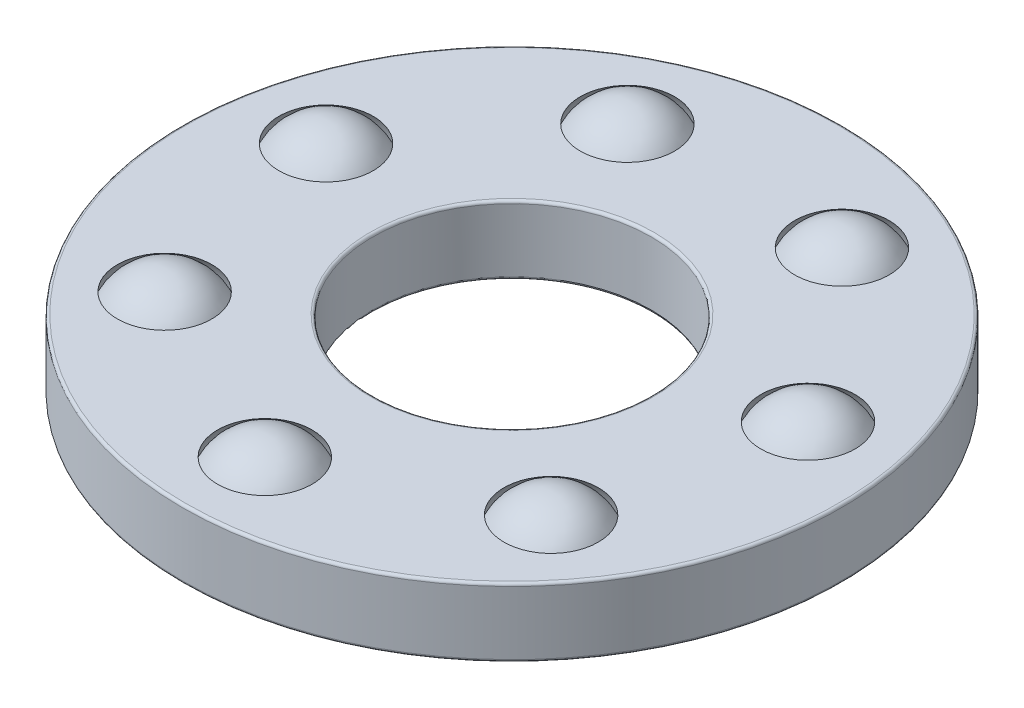
SolidWorks part; units mm, degrees
ref_plane "Front Plane" through (0, 0, 0) normal (0, 0, 1) x (1, 0, 0)
ref_plane "Top Plane" through (0, 0, 0) normal (0, 1, 0) x (1, 0, 0)
ref_plane "Right Plane" through (0, 0, 0) normal (1, 0, 0) x (0, 0, -1)
sketch "Sketch1" plane through (0, 0, 0) normal (1, 0, 0) x (0, 0, -1)
  line L0 (-6, 0) -> (6, 0) construction
  line L1 (0, -2.46) -> (0, 2.46) construction
  line L2 (-6, 0.625) -> (-2.538, 0.625)
  line L3 (-6, 0.625) -> (-6, -0.625)
  line L4 (-6, -0.625) -> (-2.538, -0.625)
  line L5 (-2.538, 0.625) -> (-2.538, -0.625)
  line L6 (-4.5, 1) -> (-4.5, -1) construction
  circle A0 centre (-4.5, 0) radius 1 construction
  dimension "D2" = 1.25
revolve "Revolve1" add sketch "Sketch1" angle 360 about L1
sketch "Sketch3" plane through (0, 0, 0) normal (1, 0, 0) x (0, 0, -1)
  line L0 (-4.5, 1.0625) -> (-4.5, -1.0625)
  line L1 (-4.5, 1) -> (-4.5, -1) construction
  line L2 (-4.4375, 1.0607) -> (-4.4375, -1.0607) construction
  arc A0 (-4.5, 1) -> (-4.5, -1) centre (-4.5, 0) ccw construction
  circle A1 centre (-4.5, 0) radius 1 construction
  arc A2 (-4.5, 1.0625) -> (-4.5, -1.0625) centre (-4.5, 0) ccw
  arc A3 (-4.4375, 1.0607) -> (-4.4375, -1.0607) centre (-4.5, 0) ccw construction
  dimension "D1" = 0.0625
revolve "Cut-Revolve1" cut sketch "Sketch3" angle 360 about L0
sketch "Sketch2" plane through (0, 0, 0) normal (1, 0, 0) x (0, 0, -1)
  line L0 (-4.5, 1) -> (-4.5, -1)
  arc A0 (-4.5, 1) -> (-4.5, -1) centre (-4.5, 0) ccw
  circle A2 centre (-4.5, 0) radius 1 construction
revolve "Revolve2" add sketch "Sketch2" angle 360 about L0
ref_axis "Axis1" through (0, 2.46, 0) along (0, -1, 0)
pattern_circular "CirPattern1" count 7 every 51.429 about axis through (0, 2.46, 0) along (0, -1, 0) of bodies 187
pattern_circular "CirPattern2" count 7 every 51.429 about axis through (0, 0, 0) along (0, 1, 0) of "Cut-Revolve1"
sketch "Sketch4" plane through (0, 0, 0) normal (1, 0, 0) x (0, 0, -1)
  line L0 (-6, 0.625) -> (-6, -0.625) construction
  line L1 (-6, 1) -> (-2.538, 1)
  line L2 (-6, 1) -> (-6, 2.46)
  line L3 (-6, 2.46) -> (-2.538, 2.46)
  line L4 (-2.538, 1) -> (-2.538, 2.46)
  line L5 (-6, -2.46) -> (-2.538, -2.46)
  line L6 (-6, -2.46) -> (-6, -1)
  line L7 (-6, -1) -> (-2.538, -1)
  line L8 (-2.538, -2.46) -> (-2.538, -1)
  line L10 (-2.538, 0.625) -> (-2.538, -0.625) construction
  line L11 (0, 0) -> (-6, 0) construction
  line L12 (-6, 0) -> (6, 0) construction
  dimension "Ht" = 4.92
  dimension "Washer Thickness" = 1.46
revolve "Revolve3" add sketch "Sketch4" angle 360 about L1
fillet "Fillet1" radius 0.0492 4 edges at (0, 1, -2.538) (0, 2.46, -2.538) (0, 1, -6) (0, 2.46, -6)
fillet "Fillet2" radius 0.0492 4 edges at (0, -0.625, -2.538) (0, 0.625, -2.538) (0, -0.625, -6) (0, 0.625, -6)
fillet "Fillet3" radius 0.0492 4 edges at (0, -2.46, -2.538) (0, -1, -2.538) (0, -2.46, -6) (0, -1, -6)
delete or keep bodies "Body-Delete/Keep 1" type delete bodies bodies 211 210
equation "\"D2@Sketch1\" = \"Roller Ball Dia@Sketch1\"*.625"
equation "\"Angle@CirPattern1\" = 360/\"Balls@CirPattern1\""
equation "\"D1@CirPattern2\" = \"Balls@CirPattern1\""
equation "\"D2@CirPattern2\" = \"Angle@CirPattern1\""
equation "\"D1@Fillet1\" = \"Th@Sketch1\"*.01"
equation "\"D1@Fillet2\" = \"D1@Fillet1\""
equation "\"D1@Fillet3\" = \"D1@Fillet1\""
